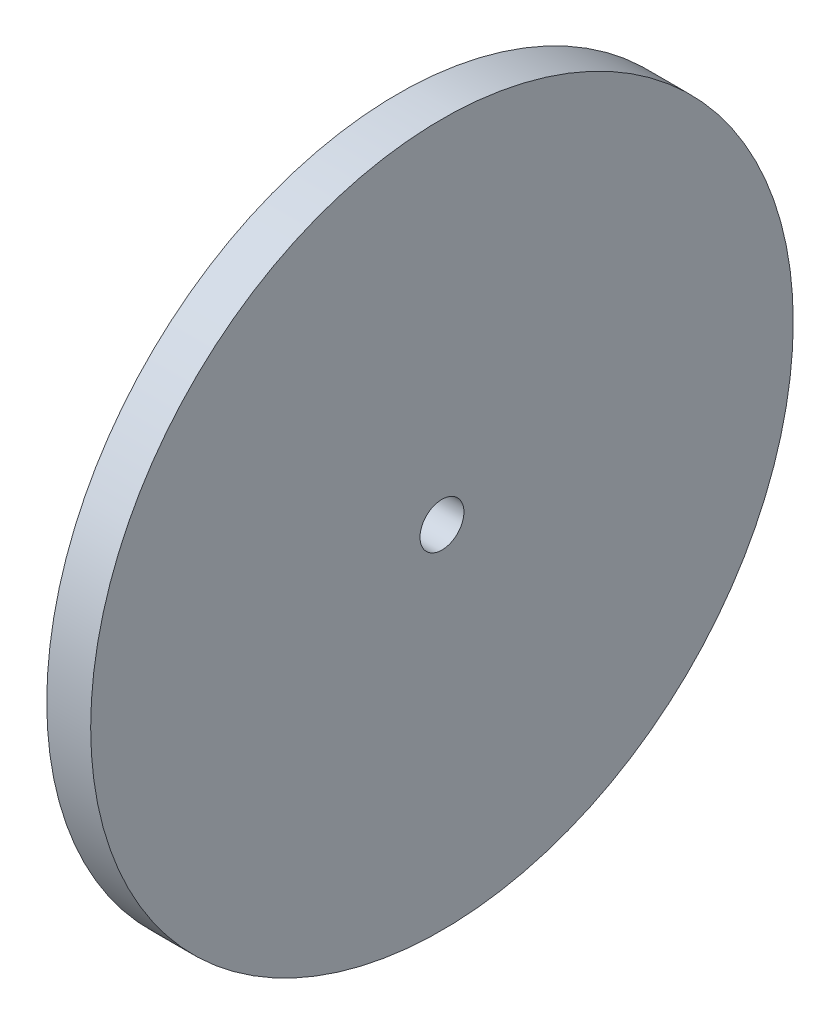
SolidWorks part; units mm, degrees
ref_plane "Front Plane" through (0, 0, 0) normal (0, 0, 1) x (1, 0, 0)
ref_plane "Top Plane" through (0, 0, 0) normal (0, 1, 0) x (1, 0, 0)
ref_plane "Right Plane" through (0, 0, 0) normal (1, 0, 0) x (0, 0, -1)
sketch "Sketch1" plane through (0, 0, 0) normal (1, 0, 0) x (0, 0, -1)
  circle A0 centre (0, 0) radius 40
  dimension "80" = 80
extrude "Boss-Extrude1" add sketch "Sketch1" along normal blind 5
sketch "Sketch2" plane through (5, 0, 0) normal (1, 0, 0) x (0, 0, -1)
  circle A0 centre (0, 0) radius 2.5
  dimension "D1" = 5
extrude "Cut-Extrude1" cut sketch "Sketch2" against normal blind 5
